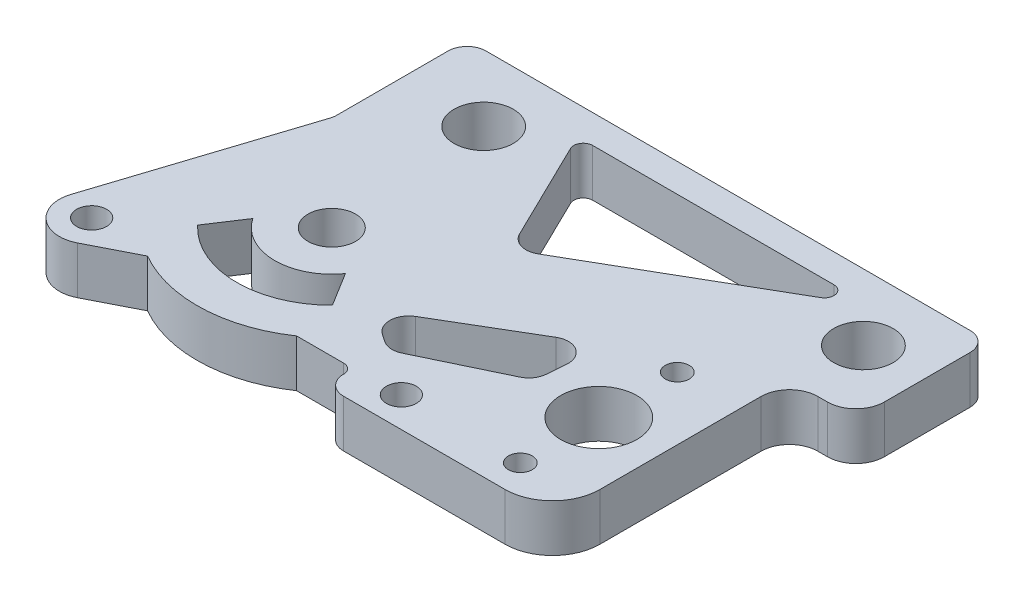
SolidWorks part; units mm, degrees
material "7075-T6 (SN)"
ref_plane "X-Y Datum" through (0, 0, 0) normal (0, 0, 1) x (1, 0, 0)
ref_plane "X-Z Datum" through (0, 0, 0) normal (0, 1, 0) x (1, 0, 0)
ref_plane "Y-Z Datum" through (0, 0, 0) normal (1, 0, 0) x (0, 0, -1)
other "Graphic1"
other "Graphic (Closed) -1"
other "Graphic (Closed) -2"
sketch "Sketch2" plane through (0, 0, 0) normal (0, 1, 0) x (1, 0, 0)
  line L0 (48.6426, -18.7325) -> (-23.0162, -18.7325)
  line L1 (24.0125, -14.7036) -> (25.7865, -13.7801) construction
  line L2 (0, 0) -> (105.5557, -202.7707) construction
  line L3 (11.142, -21.4036) -> (-3.5026, -29.027) construction
  line L4 (0, 0) -> (0, -121.3797) construction
  line L5 (-3.5026, -29.027) -> (90.9112, -210.3941) construction
  line L6 (90.9112, -210.3941) -> (105.5557, -202.7707) construction
  line L7 (11.142, -21.4036) -> (24.0125, -14.7036) construction
  line L11 (-12.7, 30.7975) -> (57.15, 30.7975)
  line L12 (57.15, 13.0175) -> (57.15, 30.7975)
  line L13 (57.15, 13.0175) -> (-12.7, 13.0175) construction
  line L15 (44.7685, -18.0975) -> (44.7685, -11.3157) construction
  line L16 (44.7685, -18.0975) -> (34.8625, -18.0975) construction
  line L18 (44.7685, 9.8425) -> (34.8625, 9.8425) construction
  line L20 (44.7685, -11.3157) -> (49.8485, -11.3157) construction
  line L21 (49.8485, -11.3157) -> (49.8485, 3.0607) construction
  line L22 (49.8485, 3.0607) -> (44.7685, 3.0607) construction
  line L23 (44.7685, 3.0607) -> (44.7685, 9.8425) construction
  line L24 (34.8625, -18.0975) -> (34.8625, 9.8425) construction
  line L25 (48.6426, -18.7325) -> (57.15, 13.0175)
  line L26 (-12.7, 30.7975) -> (-12.7, 13.0175)
  line L28 (-12.5603, 0) -> (-16.51, -40.5272) construction
  line L30 (-23.0162, -18.7325) -> (-12.7, 13.0175)
  circle A0 centre (0, 0) radius 3.175
  circle A1 centre (24.0125, -14.7036) radius 2
  circle A2 centre (-1.5875, 21.9075) radius 3.9688
  circle A3 centre (49.2125, 21.9075) radius 3.9687
  circle A4 centre (39.8485, -4.1275) radius 5.1
  circle A5 centre (24.0125, -14.7036) radius 3.175 construction
  circle A6 centre (39.8485, -14.6275) radius 1.6
  circle A7 centre (39.8485, 6.3725) radius 1.6
  circle A8 centre (-17.2047, -14.9225) radius 3.175 construction
  circle A9 centre (-17.2047, -14.9225) radius 2
  point P9 (11.142, -21.4036)
  point P30 (49.8485, -4.1275)
  point P31 (34.8625, -4.1275)
  dimension "D1" = 6.35
  dimension "D8" = 4
  dimension "D10" = 7.9375
  dimension "D11" = 7.9375
  dimension "D16" = 27.94
  dimension "D23" = 10.2
  dimension "D20" = 6.35
  dimension "D30" = 3.2
  dimension "D32" = 3.2
  dimension "D34" = 6.35
  dimension "D35" = 4
  dimension "D3" = 13.0175
  dimension "D4" = 16.51
  dimension "D5" = 228.6
  dimension "D6" = 24.13
  dimension "D7" = 27.5
  dimension "D9" = 16.51
  dimension "D12" = 8.89
  dimension "D13" = 69.85
  dimension "D14" = 7.9375
  dimension "D15" = 31.75
  dimension "D17" = 17.78
  dimension "D18" = 3.175
  dimension "D19" = 14.986
  dimension "D21" = 5.08
  dimension "D22" = 14.3764
  dimension "D24" = 10
  dimension "D25" = 36.83
  dimension "D26" = 50.8
  dimension "D27" = 165
  dimension "D28" = 12.7
  dimension "D29" = 17.3015
  dimension "D31" = 10.5
  dimension "D33" = 10.5
  dimension "D36" = 162
extrude "Boss-Extrude1" [suppressed] add sketch "Sketch2" against normal blind 6.35
ref_point "Point1" [suppressed]
sketch "Sketch3" [suppressed] plane through (0, 0, 0) normal (0, 1, 0) x (1, 0, 0)
  line L0 (39.9681, 6.3725) -> (39.9681, -4.1275) construction
  line L1 (57.2697, 12.9663) -> (-12.5803, 12.9663) construction
  line L5 (39.9681, -4.1275) -> (39.9681, -14.6275) construction
  line L6 (42.0297, -18.7325) -> (20.4164, -18.7325)
  line L7 (57.2697, 12.9663) -> (57.2697, 30.7975)
  line L8 (57.2697, 30.7975) -> (-12.5803, 30.7975)
  line L9 (-12.5803, 30.7975) -> (-12.5803, 12.9663)
  line L10 (40.938, 24.6176) -> (16.9472, 10.7666)
  line L11 (13.3942, 11.8528) -> (6.9035, 25.1608)
  line L12 (8.045, 26.9875) -> (40.303, 26.9875)
  line L13 (57.2697, 12.9663) -> (48.3797, 12.9663)
  line L14 (48.3797, 12.9663) -> (48.3797, -12.3825)
  line L16 (-23.0162, -18.7325) -> (48.6426, -18.7325) construction
  line L18 (16.6064, -14.8627) -> (10.2787, -14.8627)
  line L21 (-8.965, -15.5427) -> (-15.106, -18.7325)
  line L24 (-21.1701, -13.6017) -> (-12.5803, 12.9663)
  line L29 (17.8764, -16.1925) -> (17.8764, -16.1327)
  circle A0 centre (0.1197, 0) radius 3.175
  circle A1 centre (-1.4678, 21.9075) radius 3.9688
  circle A2 centre (49.3322, 21.9075) radius 3.9687
  circle A3 centre (39.9681, -4.1275) radius 5.1
  circle A4 centre (39.9681, -14.6275) radius 1.6
  circle A5 centre (39.9681, 6.3725) radius 1.6
  circle A6 centre (24.1322, -14.7036) radius 2
  circle A7 centre (-17.085, -14.9225) radius 2
  arc A8 (13.3942, 11.8528) -> (16.9472, 10.7666) centre (15.6772, 12.9663) ccw
  arc A9 (8.045, 26.9875) -> (6.9035, 25.1608) centre (8.045, 25.7175) ccw
  arc A10 (40.938, 24.6176) -> (40.303, 26.9875) centre (40.303, 25.7175) ccw
  arc A11 (10.2787, -14.8627) -> (-8.965, -15.5427) centre (0.1197, 0) cw
  arc A12 (-15.106, -18.7325) -> (-21.1701, -13.6017) centre (-17.085, -14.9225) cw
  arc A13 (42.0297, -18.7325) -> (48.3797, -12.3825) centre (42.0297, -12.3825) ccw
  arc A14 (20.4164, -18.7325) -> (17.8764, -16.1925) centre (20.4164, -16.1925) cw
  arc A15 (16.6064, -14.8627) -> (17.8764, -16.1327) centre (16.6064, -16.1327) cw
  dimension "D1" = 6.35
  dimension "D4" = 7.9375
  dimension "D9" = 10.2
  dimension "D10" = 3.2
  dimension "D11" = 4
  dimension "D21" = 2.54
  dimension "D22" = 1.27
  dimension "D3" = 6.35
  dimension "D28" = 2.54
  dimension "D29" = 1.27
  dimension "D2" = 7.9375
  dimension "D5" = 50.8
  dimension "D6" = 21.9075
  dimension "D7" = 1.5875
  dimension "D8" = 8.89
  dimension "D12" = 10.5
  dimension "D13" = 17.2047
  dimension "D14" = 24.0125
  dimension "D15" = 14.7036
  dimension "D16" = 39.8485
  dimension "D17" = 4.1275
  dimension "D18" = 14.9225
  dimension "D19" = 69.85
  dimension "D20" = 3.81
  dimension "D23" = 30
  dimension "D24" = 64
  dimension "D25" = 32.258
  dimension "D26" = 15.5575
  dimension "D27" = 25.3488
  dimension "D30" = 8.89
sketch "Sketch4" plane through (0, 0, 0) normal (0, 1, 0) x (1, 0, 0)
  line L0 (39.8485, 6.3725) -> (39.8485, -4.1275) construction
  line L1 (57.15, 12.9663) -> (-12.7, 12.9663) construction
  line L2 (39.8485, -4.1275) -> (39.8485, -14.6275) construction
  line L3 (41.8868, -18.7325) -> (20.2968, -18.7325)
  line L4 (57.15, 16.7763) -> (57.15, 28.2575)
  line L5 (54.61, 30.7975) -> (-10.16, 30.7975)
  line L6 (-12.7, 28.2575) -> (-12.7, 13.3678)
  line L7 (40.8183, 24.6176) -> (16.8275, 10.7666)
  line L8 (13.2746, 11.8528) -> (6.7838, 25.1608)
  line L9 (7.9253, 26.9875) -> (40.1833, 26.9875)
  line L10 (53.34, 12.9663) -> (52.07, 12.9663)
  line L11 (48.26, 9.1563) -> (48.26, -12.3825)
  line L12 (16.4868, -14.8882) -> (10.1767, -14.8882)
  line L13 (-9.0404, -15.6044) -> (-15.2421, -18.7687)
  line L14 (-21.3121, -13.5905) -> (-12.8239, 12.5843)
  line L15 (17.7568, -16.1925) -> (17.7568, -16.1582)
  line L16 (31.3257, -2.6269) -> (31.5236, -0.0707)
  line L17 (27.6993, 2.3123) -> (15.8696, -4.676)
  line L18 (15.7254, -8.958) -> (16.6997, -9.6258)
  line L19 (19.2321, -9.8219) -> (29.8897, -4.722)
  line L20 (6.2229, -4.3977) -> (9.0222, -8.9381)
  line L21 (-6.35, -4.2121) -> (-9.282, -8.668)
  circle A0 centre (0, 0) radius 3.175
  circle A1 centre (-1.5875, 21.9075) radius 3.9688
  circle A2 centre (49.2125, 21.9075) radius 3.9687
  circle A3 centre (39.8485, -4.1275) radius 5.1
  circle A4 centre (39.8485, -14.6275) radius 1.6
  circle A5 centre (39.8485, 6.3725) radius 1.6
  circle A6 centre (24.0125, -14.7036) radius 2
  circle A7 centre (-17.2047, -14.9225) radius 2
  arc A8 (13.2746, 11.8528) -> (16.8275, 10.7666) centre (15.5575, 12.9663) ccw
  arc A9 (7.9253, 26.9875) -> (6.7838, 25.1608) centre (7.9253, 25.7175) ccw
  arc A10 (40.8183, 24.6176) -> (40.1833, 26.9875) centre (40.1833, 25.7175) ccw
  arc A11 (10.1767, -14.8882) -> (-9.0404, -15.6044) centre (0, 0) cw
  arc A12 (-15.2421, -18.7687) -> (-21.3121, -13.5905) centre (-17.2047, -14.9225) cw
  arc A13 (41.8868, -18.7325) -> (48.26, -12.3825) centre (41.91, -12.3825) ccw
  arc A14 (20.2968, -18.7325) -> (17.7568, -16.1925) centre (20.2968, -16.1925) cw
  arc A15 (16.4868, -14.8882) -> (17.7568, -16.1582) centre (16.4868, -16.1582) cw
  arc A16 (57.15, 16.7763) -> (53.34, 12.9663) centre (53.34, 16.7763) cw
  arc A17 (48.26, 9.1563) -> (52.07, 12.9663) centre (52.07, 9.1563) cw
  arc A18 (-12.7, 13.3678) -> (-12.8239, 12.5843) centre (-15.24, 13.3678) cw
  arc A19 (-12.7, 28.2575) -> (-10.16, 30.7975) centre (-10.16, 28.2575) cw
  arc A20 (54.61, 30.7975) -> (57.15, 28.2575) centre (54.61, 28.2575) cw
  arc A21 (16.6997, -9.6258) -> (19.2321, -9.8219) centre (18.1357, -7.5307) ccw
  arc A22 (29.8897, -4.722) -> (31.3257, -2.6269) centre (28.7933, -2.4308) ccw
  arc A23 (15.8696, -4.676) -> (15.7254, -8.958) centre (17.1615, -6.8629) ccw
  arc A24 (27.6993, 2.3123) -> (31.5236, -0.0707) centre (28.9912, 0.1254) cw
  arc A25 (6.2229, -4.3977) -> (-6.35, -4.2121) centre (0, 0) cw
  arc A26 (9.0222, -8.9381) -> (-9.282, -8.668) centre (0, 0) cw
  point P52 (48.26, 12.9663)
  point P58 (-12.7, 30.7975)
  point P61 (57.15, 30.7975)
  point P66 (17.9093, -10.4549)
  point P69 (31.2125, -4.089)
  point P72 (12.4368, -6.7039)
  point P75 (31.9003, 4.794)
  dimension "D1" = 6.35
  dimension "D2" = 7.9375
  dimension "D6" = 10.2
  dimension "D7" = 3.2
  dimension "D8" = 4
  dimension "D19" = 2.54
  dimension "D20" = 1.27
  dimension "D25" = 6.35
  dimension "D26" = 2.54
  dimension "D27" = 1.27
  dimension "D31" = 18.034
  dimension "D33" = 4.318
  dimension "D37" = 3.81
  dimension "D38" = 3.81
  dimension "D39" = 2.54
  dimension "D48" = 2.54
  dimension "D49" = 2.54
  dimension "D50" = 7.62
  dimension "D51" = 12.7
  dimension "D3" = 50.8
  dimension "D4" = 21.9075
  dimension "D5" = 1.5875
  dimension "D9" = 10.5
  dimension "D10" = 24.0125
  dimension "D11" = 14.7036
  dimension "D12" = 39.8485
  dimension "D13" = 4.1275
  dimension "D14" = 14.9225
  dimension "D15" = 17.2047
  dimension "D16" = 7.9375
  dimension "D17" = 8.89
  dimension "D18" = 3.81
  dimension "D21" = 30
  dimension "D22" = 64
  dimension "D23" = 32.258
  dimension "D24" = 15.5575
  dimension "D28" = 25.3488
  dimension "D29" = 8.89
  dimension "D30" = 21.59
  dimension "D32" = 45
  dimension "D34" = 69.85
  dimension "D35" = 23.0847
  dimension "D36" = 25.9645
  dimension "D40" = 55
  dimension "D41" = 65
  dimension "D42" = 120
  dimension "D43" = 8.636
  dimension "D44" = 22.606
  dimension "D45" = 4.2487
  dimension "D46" = 14.7479
  dimension "D47" = 31.9003
  dimension "D52" = 5.334
  dimension "D53" = 65
  dimension "D54" = 6.35
extrude "Boss-Extrude2" add sketch "Sketch4" against normal blind 6.35
ref_point "Point2"
ref_point "Point3"
sketch "Sketch5" plane through (0, 0, 0) normal (0, 1, 0) x (1, 0, 0)
  line L0 (0, 0) -> (0, -33.6075) construction
  line L1 (0, 0) -> (21.4023, -37.0699) construction
  dimension "D1" = 30
